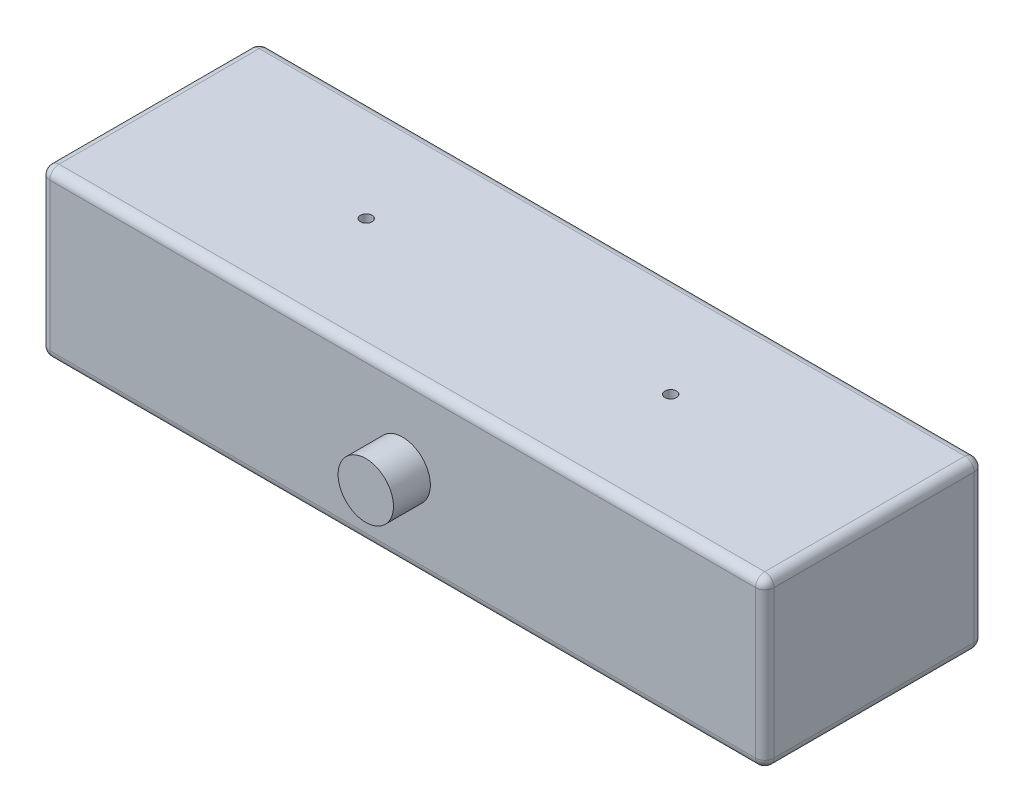
SolidWorks part; units mm, degrees
ref_plane "前视基准面" through (0, 0, 0) normal (0, 0, 1) x (1, 0, 0)
ref_plane "上视基准面" through (0, 0, 0) normal (0, 1, 0) x (1, 0, 0)
ref_plane "右视基准面" through (0, 0, 0) normal (1, 0, 0) x (0, 0, -1)
sketch "草图1" plane through (0, 0, 0) normal (1, 0, 0) x (0, 0, -1)
  line L1 (-23.7, -18) -> (23.7, -18)
  line L2 (-23.7, -18) -> (-23.7, 18)
  line L3 (-23.7, 18) -> (23.7, 18)
  line L4 (23.7, -18) -> (23.7, 18)
  line L5 (-23.7, -18) -> (23.7, 18) construction
  line L6 (-23.7, 18) -> (23.7, -18) construction
  point P0 (0, 0)
  dimension "D1" = 36
  dimension "D2" = 47.4
extrude "凸台-拉伸1" add sketch "草图1" along normal mid plane 157
fillet "圆角1" radius 2 12 edges at (-78.5, 0, 23.7) (-78.5, 0, -23.7) (78.5, 0, 23.7) (78.5, 0, -23.7) (0, -18, 23.7) (78.5, -18, 0) (0, -18, -23.7) (-78.5, -18, 0) (0, 18, -23.7) (78.5, 18, 0) (0, 18, 23.7) (-78.5, 18, 0)
hole_wizard "M3 螺纹孔1" positions "草图3" profile "草图2" tap size "M3" standard "GB"
sketch "草图3" plane through (0, 18, 41.7) normal (0, 1, 0) x (1, 0, 0)
  line L0 (0, 41.7) -> (0, 43.5329) construction
  line L4 (-76.5, 65.4) -> (76.5, 65.4) construction
  point P0 (-33, 43.1)
  point P2 (33, 43.1)
  dimension "D1" = 66
  dimension "D2" = 22.3
sketch "草图2" plane through (-33, 18, -1.4) normal (1, 0, 0) x (0, 0, 1)
  line L0 (0, 0) -> (0, 4.7511)
  line L1 (0, 4.7511) -> (1.25, 4)
  line L2 (1.25, 4) -> (1.25, 0)
  line L5 (1.25, 0) -> (0, 0)
  line L10 (0, 4.7511) -> (-1.25, 4) construction
  line L11 (0, -6.35) -> (0, 107.95) construction
  dimension "螺纹孔钻头直径" = 2.5
  dimension "螺纹孔钻头深度" = 4
  dimension "导头角度" = 118
cosmetic thread "孔螺蚊线3" parameters "D1"=4, "D2"=3
cosmetic thread "孔螺蚊线4" parameters "D1"=4, "D2"=3
sketch "草图4" plane through (0, 0, -23.7) normal (0, 0, -1) x (-1, 0, 0)
  line L0 (0, 0) -> (0, 28.5415) construction
  circle A0 centre (60, 0) radius 9
  circle A1 centre (-60, 0) radius 9
  dimension "D1" = 120
  dimension "D2" = 18
extrude "切除-拉伸1" cut sketch "草图4" against normal blind 2
sketch "草图5" plane through (0, 0, 23.7) normal (0, 0, 1) x (1, 0, 0)
  circle A0 centre (0, 0) radius 6
  dimension "D1" = 12
extrude "凸台-拉伸2" add sketch "草图5" along normal blind 8
